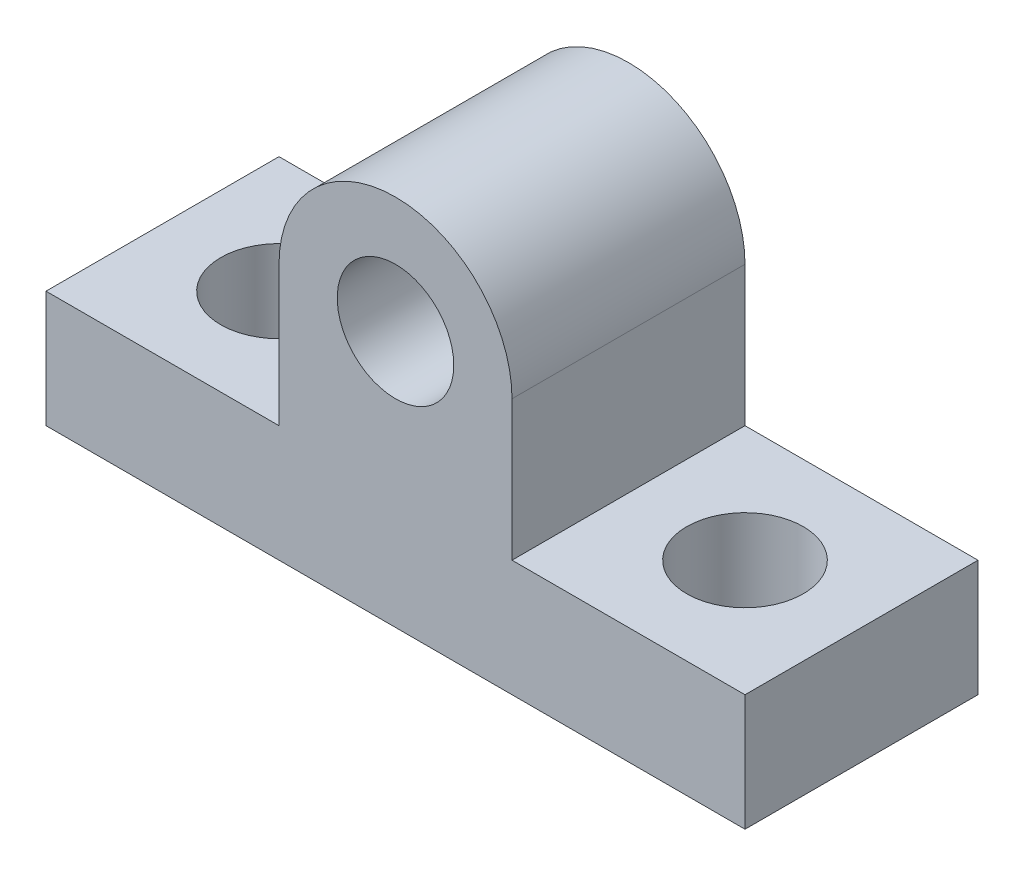
SolidWorks part; units mm, degrees
ref_plane "前视基准面" through (0, 0, 0) normal (0, 0, 1) x (1, 0, 0)
ref_plane "上视基准面" through (0, 0, 0) normal (0, 1, 0) x (1, 0, 0)
ref_plane "右视基准面" through (0, 0, 0) normal (1, 0, 0) x (0, 0, -1)
sketch "草图1" plane through (0, 0, 0) normal (0, 0, 1) x (1, 0, 0)
  line L0 (5, 0) -> (15, 0)
  line L1 (15, 0) -> (15, -5)
  line L2 (15, -5) -> (-15, -5)
  line L4 (5, 6) -> (5, 0)
  line L5 (-15, 0) -> (-15, -5)
  line L6 (-5, 0) -> (-15, 0)
  line L7 (-5, 6) -> (-5, 0)
  arc A0 (5, 6) -> (-5, 6) centre (0, 6) ccw
  circle A1 centre (0, 6) radius 2.5
  point P11 (0, -5)
  dimension "D3" = 10
  dimension "D4" = 5
  dimension "D1" = 6
  dimension "D2" = 5
extrude "凸台-拉伸1" add sketch "草图1" along normal blind 10
sketch "草图2" plane through (0, 0, 0) normal (0, 1, 0) x (1, 0, 0)
  line L0 (-5, 0) -> (-15, 0) construction
  line L4 (-15, -10) -> (-15, 0) construction
  circle A0 centre (-10, -5) radius 2.5
  dimension "D1" = 5
  dimension "D2" = 5
extrude "切除-拉伸1" cut sketch "草图2" against normal blind 5 contours A0
sketch "草图3" plane through (0, 0, 0) normal (0, 1, 0) x (1, 0, 0)
  line L0 (15, -10) -> (15, 0) construction
  line L1 (15, -10) -> (5, -10) construction
  circle A0 centre (10, -5) radius 2.5
  dimension "D1" = 5
  dimension "D2" = 5
  dimension "D3" = 5
extrude "切除-拉伸2" cut sketch "草图3" against normal blind 5 contours A0
